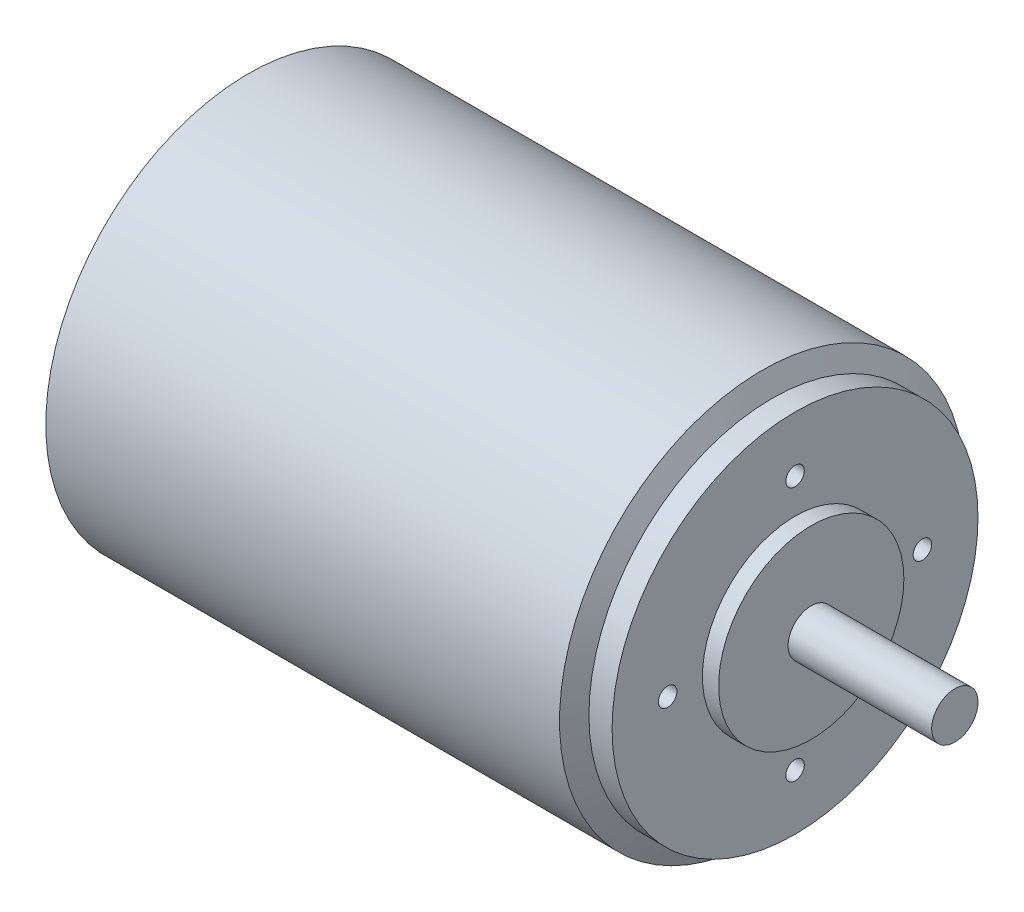
SolidWorks part; units mm, degrees
ref_plane "Plan de face" through (0, 0, 0) normal (0, 0, 1) x (1, 0, 0)
ref_plane "Plan de dessus" through (0, 0, 0) normal (0, 1, 0) x (1, 0, 0)
ref_plane "Plan de droite" through (0, 0, 0) normal (1, 0, 0) x (0, 0, -1)
sketch "Esquisse1" plane through (0, 0, 0) normal (0, 1, 0) x (1, 0, 0)
  line L0 (-18.4601, 0) -> (-18.4601, 2)
  line L1 (-18.4601, 2) -> (-12.1601, 2)
  line L2 (-12.1601, 2) -> (-12.1601, 7)
  line L3 (-12.1601, 7) -> (-8.6601, 7)
  line L4 (-8.6601, 7) -> (-8.6601, 17.5)
  line L5 (-8.6601, 17.5) -> (35.7035, 17.5)
  line L6 (35.7035, 17.5) -> (36.5399, 15.8)
  line L7 (36.5399, 15.8) -> (38.5399, 15.8)
  line L8 (38.5399, 15.8) -> (38.5399, 8)
  line L9 (38.5399, 8) -> (39.9399, 8)
  line L10 (39.9399, 8) -> (39.9399, 2)
  line L11 (39.9399, 2) -> (52.3399, 2)
  line L12 (52.3399, 2) -> (52.3399, 0)
  line L13 (52.3399, 0) -> (-18.4601, 0)
  dimension "D1" = 17.5
  dimension "D2" = 15.8
  dimension "D3" = 8
  dimension "D4" = 2
  dimension "D5" = 1.4
  dimension "D6" = 12.4
  dimension "D7" = 2
  dimension "D8" = 70.8
  dimension "D9" = 3.5
  dimension "D10" = 6.3
  dimension "D11" = 7
  dimension "D12" = 2
revolve "Révolution1" add sketch "Esquisse1" angle 360 about L13
sketch "Esquisse2" plane through (38.5399, 0, 0) normal (1, 0, 0) x (0, 0, -1)
  circle A0 centre (11, 0) radius 1
  dimension "D2" = 2
  dimension "D1" = 11
hole_wizard "Trou taraudé M22" positions "Esquisse3D2" profile "Esquisse4" tap size "M2" standard "ISO"
sketch3d "Esquisse3D2"
  point P0 (38.5399, 0, -11)
sketch "Esquisse4" plane through (38.5399, 0, -11) normal (0, 1, 0) x (0, 0, -1)
  line L0 (0, 0) -> (0, 5.1807)
  line L1 (0, 5.1807) -> (0.8, 4.7)
  line L2 (0.8, 4.7) -> (0.8, 0)
  line L5 (0.8, 0) -> (0, 0)
  line L10 (0, 5.1807) -> (-0.8, 4.7) construction
  line L11 (0, -6.35) -> (0, 107.95) construction
  dimension "Diamètre du trou pour taraudage" = 1.6
  dimension "Profondeur du trou pour taraudage" = 4.7
  dimension "Angle de pointe" = 118
cosmetic thread "Filetage de perçage2" parameters "D1"=3.5, "D2"=2
pattern_circular "Répétition circulaire7" count 4 over 360 about axis through (0, 0, 0) along (1, 0, 0) of "Trou taraudé M22"
